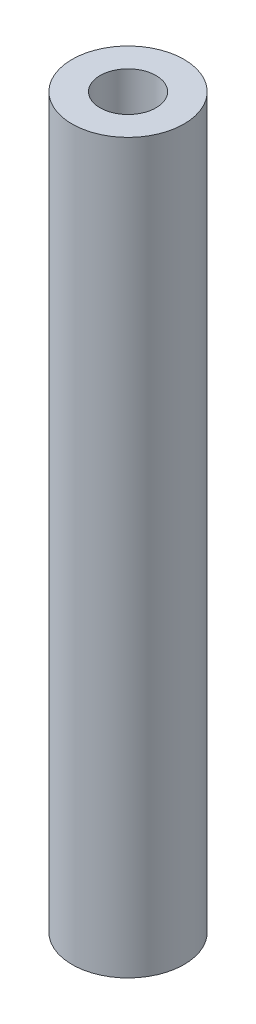
SolidWorks part; units mm, degrees
ref_plane "Plan de face" through (0, 0, 0) normal (0, 0, 1) x (1, 0, 0)
ref_plane "Plan de dessus" through (0, 0, 0) normal (0, 1, 0) x (1, 0, 0)
ref_plane "Plan de droite" through (0, 0, 0) normal (1, 0, 0) x (0, 0, -1)
sketch "Esquisse1" plane through (0, 0, 0) normal (0, 0, 1) x (1, 0, 0)
  line L0 (0, 0) -> (0, 65)
  dimension "D1" = 65
revolve "Révol.-Mince1" add sketch "Esquisse1" angle 360 about L0 wall 5
sketch "Esquisse2" plane through (0, 65, 0) normal (0, 1, 0) x (1, 0, 0)
  circle A0 centre (0, 0) radius 2.5
  dimension "D1" = 5
extrude "Enlèv. mat.-Extru.1" cut sketch "Esquisse2" against normal through all
